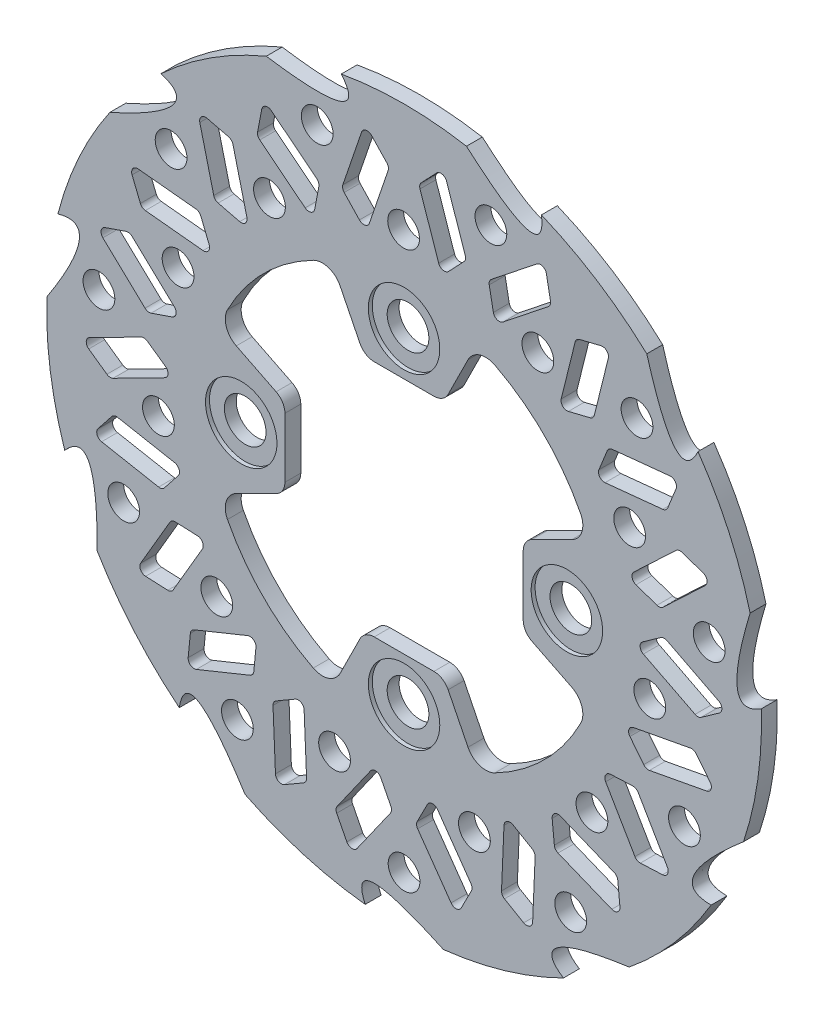
SolidWorks part; units mm, degrees
material "AISI 1045 Steel, cold drawn"
ref_plane "Front Plane" through (0, 0, 0) normal (0, 0, 1) x (1, 0, 0)
ref_plane "Top Plane" through (0, 0, 0) normal (0, 1, 0) x (1, 0, 0)
ref_plane "Right Plane" through (0, 0, 0) normal (1, 0, 0) x (0, 0, -1)
sketch "Sketch1" plane through (0, 0, 0) normal (0, 0, 1) x (1, 0, 0)
  circle A0 centre (0, 0) radius 90
  circle A1 centre (0, 0) radius 50
  dimension "D1" = 180
  dimension "D2" = 100
extrude "Boss-Extrude1" add sketch "Sketch1" along normal blind 4
sketch "Sketch2" plane through (0, 0, 0) normal (0, 0, 1) x (1, 0, 0)
  line L0 (0, 0) -> (0, -90) construction
  line L1 (-20, -50.0723) -> (20, -50.0723)
  line L2 (-10, -30) -> (10, -30)
  line L3 (10, -30) -> (20, -50.0723)
  line L4 (-10, -30) -> (-20, -50.0723)
  circle A0 centre (0, 0) radius 90 construction
  dimension "D1" = 40
  dimension "D2" = 20
  dimension "D3" = 20
  dimension "D4" = 10
  dimension "D5" = 30
extrude "Boss-Extrude2" add sketch "Sketch2" along normal blind 4
sketch "Sketch3" plane through (0, 0, 4) normal (0, 0, 1) x (1, 0, 0)
  circle A0 centre (0, -41) radius 5.25
  dimension "D1" = 10.5
  dimension "D2" = 41
extrude "Cut-Extrude1" cut sketch "Sketch3" against normal blind 4
fillet "Fillet1" radius 4 2 edges at (10, -30, 2) (-10, -30, 2)
fillet "Fillet2" radius 5 2 edges at (18.2461, -46.5519, 2) (-18.2461, -46.5519, 2)
pattern_circular "CirPattern1" count 4 over 360 about axis through (0, 0, 0) along (0, 0, 1) of "Fillet2", "Fillet1", "Cut-Extrude1", "Boss-Extrude2"
sketch "Sketch4" plane through (0, 0, 4) normal (0, 0, 1) x (1, 0, 0)
  line L0 (0, 0) -> (0, -90) construction
  line L1 (-16.8463, -71.6081) -> (-8.4304, -59.6647)
  line L2 (-16.9555, -73.1553) -> (-14.4061, -78.138)
  line L3 (-5.8689, -59.8455) -> (-3.3196, -64.8281)
  line L4 (-11.8446, -78.3188) -> (-3.4288, -66.3754)
  line L5 (11.8446, -78.3188) -> (3.4288, -66.3754)
  line L6 (16.9555, -73.1553) -> (14.4061, -78.138)
  line L7 (5.8689, -59.8455) -> (3.3196, -64.8281)
  line L8 (16.8463, -71.6081) -> (8.4304, -59.6647)
  circle A0 centre (0, 0) radius 90 construction
  circle A1 centre (0, -77.62) radius 4
  circle A2 centre (-17.5, -60) radius 4
  arc A3 (-16.9555, -73.1553) -> (-16.8463, -71.6081) centre (-15.6201, -72.4721) cw
  arc A4 (-14.4061, -78.138) -> (-11.8446, -78.3188) centre (-13.0708, -77.4547) ccw
  arc A5 (-3.3196, -64.8281) -> (-3.4288, -66.3754) centre (-4.6549, -65.5114) cw
  arc A6 (-8.4304, -59.6647) -> (-5.8689, -59.8455) centre (-7.2043, -60.5287) cw
  arc A7 (14.4061, -78.138) -> (11.8446, -78.3188) centre (13.0708, -77.4547) cw
  arc A8 (16.9555, -73.1553) -> (16.8463, -71.6081) centre (15.6201, -72.4721) ccw
  arc A9 (8.4304, -59.6647) -> (5.8689, -59.8455) centre (7.2043, -60.5287) ccw
  arc A10 (3.3196, -64.8281) -> (3.4288, -66.3754) centre (4.6549, -65.5114) ccw
  spline S0 degree 2 poles (-9.7824, -89.4668) (-14.8999, -77.9737) (9.8937, -89.4545) knots 0 0 0 1 1 1
  point P14 (-17.3681, -72.3487)
  point P18 (-13.275, -80.3487)
  point P22 (-2.9069, -65.6347)
  point P25 (-7, -57.6347)
  point P29 (-10.5347, -89.3813)
  point P36 (17.3681, -72.3487)
  point P42 (7, -57.6347)
  point P43 (2.9069, -65.6347)
  point P45 (9.931, -89.4504)
  point P46 (0, 0)
  point P47 (0, 0)
  circle M40 centre (0, 0) radius 90
  dimension "D1" = 8
  dimension "D2" = 8
  dimension "D9" = 1.5
  dimension "D10" = 1.5
  dimension "D3" = 77.62
  dimension "D4" = 60
  dimension "D5" = 17.5
  dimension "D6" = 8
  dimension "D7" = 18
  dimension "D8" = 7
extrude "Cut-Extrude2" cut sketch "Sketch4" against normal blind 4 contours L7 A10 L5 A7 L6 A8 L8 A9 | A6 L1 A3 L2 A4 L4 A5 L3 | L0 A1 | A1 L0 | L0 S0 M40 | S0 L0 M40 | A2
pattern_circular "CirPattern2" count 11 over 360 of "Cut-Extrude2"
sketch "Sketch5" plane through (0, 0, 4) normal (0, 0, 1) x (1, 0, 0)
  circle A0 centre (0, -41) radius 9
  dimension "D1" = 18
extrude "Cut-Extrude3" cut sketch "Sketch5" against normal blind 1
pattern_circular "CirPattern3" count 4 over 360 about axis through (0, 0, 0) along (0, 0, 1) of "Cut-Extrude3"
